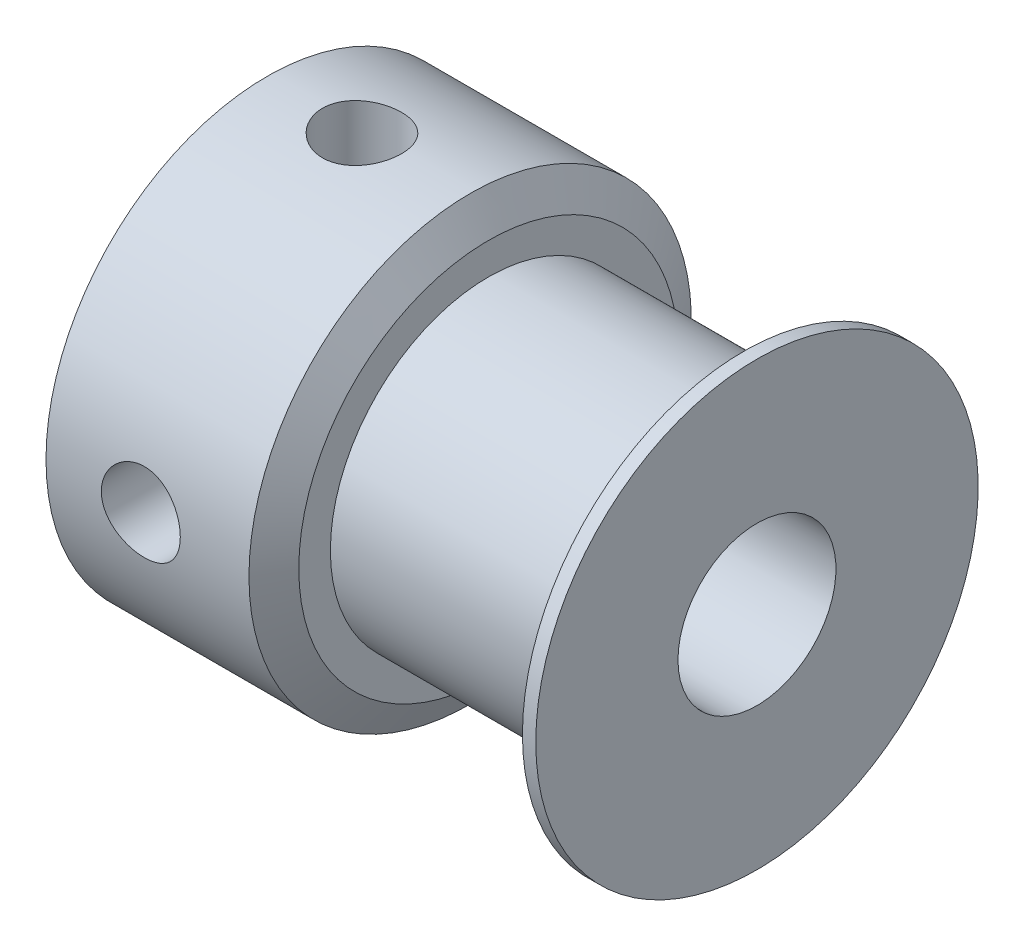
SolidWorks part; units mm, degrees
ref_plane "Plan de face" through (0, 0, 0) normal (0, 0, 1) x (1, 0, 0)
ref_plane "Plan de dessus" through (0, 0, 0) normal (0, 1, 0) x (1, 0, 0)
ref_plane "Plan de droite" through (0, 0, 0) normal (1, 0, 0) x (0, 0, -1)
sketch "Esquisse1" plane through (0, 0, 0) normal (0, 0, 1) x (1, 0, 0)
  line L0 (0, 2.5) -> (0, 7)
  line L1 (0, 7) -> (6.4226, 7)
  line L2 (6.4226, 7) -> (7, 6)
  line L3 (7, 6) -> (7, 5)
  line L4 (7, 5) -> (14.5, 5)
  line L5 (14.5, 5) -> (14.5, 6)
  line L6 (14.5, 6) -> (15.0774, 7)
  line L7 (15.0774, 7) -> (15.5, 7)
  line L8 (15.5, 7) -> (15.5, 2.5)
  line L9 (0, 0) -> (13.8, 0) construction
  line L10 (0, 2.5) -> (15.5, 2.5)
  dimension "D1" = 2.5
  dimension "D2" = 15.5
  dimension "D3" = 7
  dimension "D4" = 7.5
  dimension "D5" = 7
  dimension "D6" = 7
  dimension "D7" = 15.5
  dimension "D8" = 5
  dimension "D9" = 1
  dimension "D10" = 1
  dimension "D11" = 30
  dimension "D12" = 30
revolve "Révolution1" add sketch "Esquisse1" angle 360 about L9
hole_wizard "Trou taraudé M31" positions "Esquisse3" profile "Esquisse2" tap size "M3" standard "ISO"
sketch "Esquisse3" plane through (0, 0, 0) normal (0, 0, 1) x (1, 0, 0)
  point P0 (3, 0)
  dimension "D1" = 3
sketch "Esquisse2" plane through (3, 0, 0) normal (1, 0, 0) x (0, 1, 0)
  line L0 (0, 0) -> (0, 7)
  line L1 (0, 7) -> (1.25, 7)
  line L2 (1.25, 7) -> (1.25, 0)
  line L5 (1.25, 0) -> (0, 0)
  line L11 (0, -6.35) -> (0, 107.95) construction
  dimension "Diamètre du trou pour taraudage jusqu'au prochain" = 2.5
  dimension "Profondeur du trou pour taraudage jusqu'au prochain" = 7
cosmetic thread "Filetage de perçage1" parameters "D2"=3
hole_wizard "Trou taraudé M32" positions "Esquisse6" profile "Esquisse5" tap size "M3" standard "ISO"
sketch "Esquisse6" plane through (0, 0, 0) normal (0, 1, 0) x (1, 0, 0)
  point P0 (3, 0)
  dimension "D1" = 3
sketch "Esquisse5" plane through (3, 0, 0) normal (1, 0, 0) x (0, 0, -1)
  line L0 (0, 0) -> (0, 7)
  line L1 (0, 7) -> (1.25, 7)
  line L2 (1.25, 7) -> (1.25, 0)
  line L5 (1.25, 0) -> (0, 0)
  line L11 (0, -6.35) -> (0, 107.95) construction
  dimension "Diamètre du trou pour taraudage jusqu'au prochain" = 2.5
  dimension "Profondeur du trou pour taraudage jusqu'au prochain" = 7
cosmetic thread "Filetage de perçage2" parameters "D2"=3
